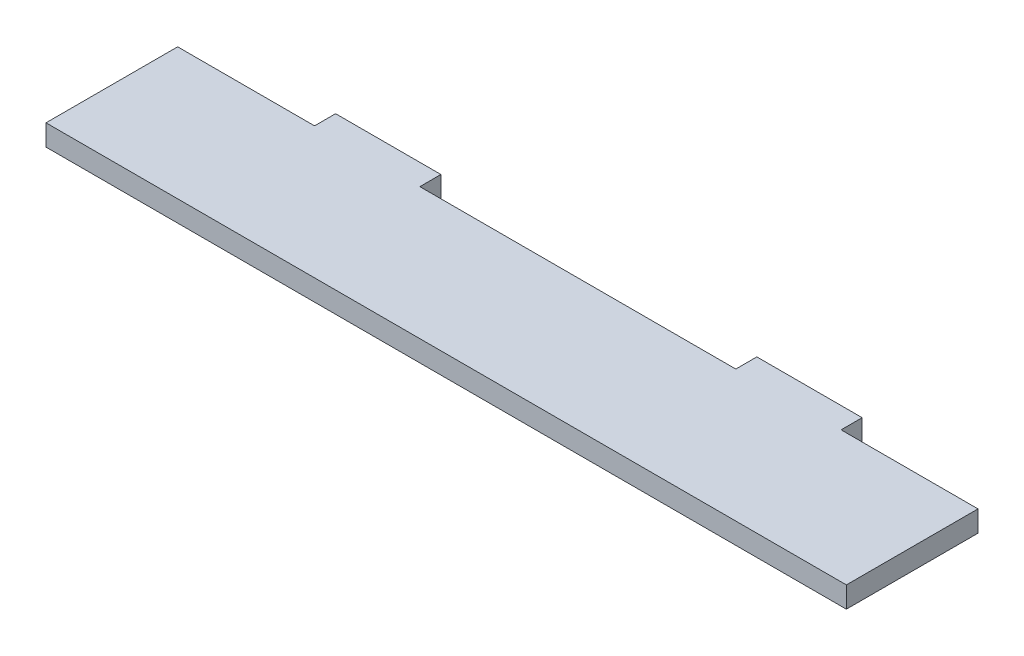
SolidWorks part; units mm, degrees
ref_plane "Front Plane" through (0, 0, 0) normal (0, 0, 1) x (1, 0, 0)
ref_plane "Top Plane" through (0, 0, 0) normal (0, 1, 0) x (1, 0, 0)
ref_plane "Right Plane" through (0, 0, 0) normal (1, 0, 0) x (0, 0, -1)
sketch "Sketch1" plane through (0, 0, 0) normal (0, 0, 1) x (1, 0, 0)
  line L0 (-96.52, 152.4) -> (-96.52, 177.8) construction
  line L1 (-96.52, 106.68) -> (96.52, 106.68)
  line L2 (-96.52, 106.68) -> (-96.52, 101.6)
  line L3 (-96.52, 101.6) -> (96.52, 101.6)
  line L4 (96.52, 106.68) -> (96.52, 101.6)
  line L6 (96.52, 50.8) -> (96.52, 198.12) construction
  line L7 (-63.5, 106.68) -> (-38.1, 106.68) construction
  line L9 (-63.5, 106.68) -> (-38.1, 106.68)
  line L10 (-63.5, 106.68) -> (-63.5, 101.6)
  line L11 (-63.5, 101.6) -> (-38.1, 101.6)
  line L12 (-38.1, 106.68) -> (-38.1, 101.6)
  line L13 (38.1, 106.68) -> (63.5, 106.68)
  line L14 (38.1, 106.68) -> (38.1, 101.6)
  line L15 (38.1, 101.6) -> (63.5, 101.6)
  line L16 (63.5, 106.68) -> (63.5, 101.6)
  dimension "D1" = 5.08
extrude "Boss-Extrude1" add sketch "Sketch1" along normal blind 31.75 contours L3 L4 L1 L2
sketch "Sketch4" plane through (0, 0, 0) normal (0, 0, -1) x (-1, 0, 0)
  line L0 (96.52, 101.6) -> (-96.52, 101.6) construction
  line L1 (63.5, 101.6) -> (38.1, 101.6)
  line L2 (63.5, 101.6) -> (63.5, 106.68)
  line L3 (63.5, 106.68) -> (38.1, 106.68)
  line L4 (38.1, 101.6) -> (38.1, 106.68)
  line L5 (63.5, 101.6) -> (63.5, 106.68) construction
  line L6 (96.52, 106.68) -> (-96.52, 106.68) construction
  line L7 (38.1, 101.6) -> (38.1, 106.68) construction
  line L8 (-38.1, 101.6) -> (-38.1, 106.68) construction
  line L9 (-38.1, 101.6) -> (-63.5, 101.6)
  line L10 (-38.1, 101.6) -> (-38.1, 106.68)
  line L11 (-38.1, 106.68) -> (-63.5, 106.68)
  line L12 (-63.5, 101.6) -> (-63.5, 106.68)
  dimension "D1" = 25.4
extrude "Boss-Extrude2" add sketch "Sketch4" along normal blind 5.08
